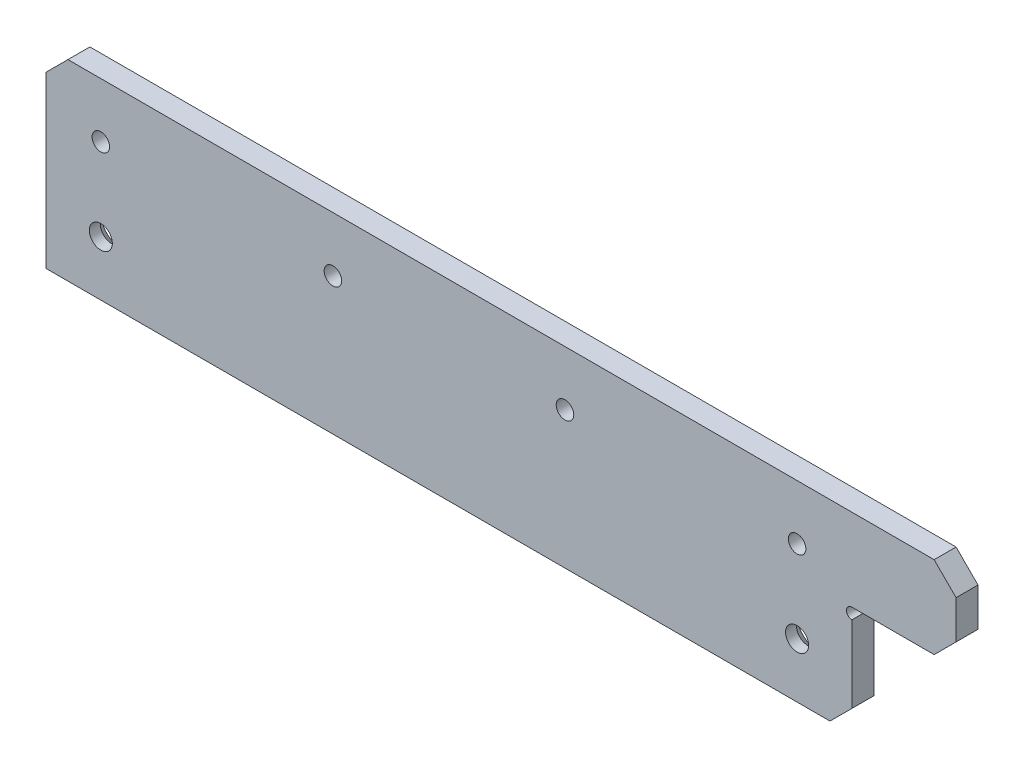
SolidWorks part; units mm, degrees
ref_plane "前视基准面" through (0, 0, 0) normal (0, 0, 1) x (1, 0, 0)
ref_plane "上视基准面" through (0, 0, 0) normal (0, 1, 0) x (1, 0, 0)
ref_plane "右视基准面" through (0, 0, 0) normal (1, 0, 0) x (0, 0, -1)
sketch "草图1" plane through (0, 0, 0) normal (0, 0, 1) x (1, 0, 0)
  line L1 (73.5, -17.5) -> (-73.5, -17.5)
  line L2 (73.5, -17.5) -> (73.5, 17.5)
  line L3 (73.5, 17.5) -> (-73.5, 17.5)
  line L4 (-73.5, -17.5) -> (-73.5, 17.5)
  line L5 (73.5, -17.5) -> (-73.5, 17.5) construction
  line L6 (73.5, 17.5) -> (-73.5, -17.5) construction
  point P0 (0, 0)
  dimension "D1" = 35
  dimension "D2" = 147
extrude "凸台-拉伸1" add sketch "草图1" along normal mid plane 4
sketch "草图2" plane through (0, 0, 2) normal (0, 0, 1) x (1, 0, 0)
  line L1 (73.5, 17.5) -> (92.5, 17.5)
  line L2 (73.5, 17.5) -> (73.5, 2.5)
  line L3 (73.5, 2.5) -> (92.5, 2.5)
  line L4 (92.5, 17.5) -> (92.5, 2.5)
  dimension "D1" = 15
  dimension "D2" = 19
extrude "凸台-拉伸2" add sketch "草图2" against normal blind 4
sketch "草图3" plane through (0, 0, 2) normal (0, 0, 1) x (1, 0, 0)
  line L0 (-63.5, -7.5) -> (63.5, -7.5) construction
  line L1 (-73.5, 17.5) -> (-73.5, -17.5) construction
  line L2 (-73.5, -17.5) -> (73.5, -17.5) construction
  line L3 (73.5, -17.5) -> (73.5, 2.5) construction
  circle A0 centre (-63.5, -7.5) radius 2.1
  circle A1 centre (63.5, -7.5) radius 2.1
  dimension "D1" = 4.2
  dimension "D2" = 10
  dimension "D4" = 10
  dimension "D3" = 10
extrude "切除-拉伸1" cut sketch "草图3" against normal through all
chamfer "倒角1" distance 4 angle 45 4 edges at (92.5, 2.5, 0) (73.5, -17.5, 0) (-73.5, 17.5, 0) (92.5, 17.5, 0)
sketch "草图4" plane through (0, 0, 2) normal (0, 0, 1) x (1, 0, 0)
  line L0 (73.5, -13.5) -> (73.5, 2.5) construction
  circle A0 centre (73.5, 1.5) radius 1
  dimension "D1" = 2
extrude "切除-拉伸2" cut sketch "草图4" against normal through all
sketch "草图5" plane through (0, 0, 2) normal (0, 0, 1) x (1, 0, 0)
  line L0 (-63.5, 7.5) -> (-21.1667, 7.5) construction
  line L1 (-21.1667, 7.5) -> (21.1667, 7.5) construction
  line L2 (21.1667, 7.5) -> (63.5, 7.5) construction
  line L3 (-73.5, 13.5) -> (-73.5, -17.5) construction
  line L4 (-73.5, -17.5) -> (69.5, -17.5) construction
  circle A0 centre (-63.5, 7.5) radius 1.6
  circle A1 centre (-21.1667, 7.5) radius 1.6
  circle A2 centre (21.1667, 7.5) radius 1.6
  circle A3 centre (63.5, 7.5) radius 1.6
  point P8 (0, 7.5)
  dimension "D1" = 3.2
  dimension "D2" = 10
  dimension "D3" = 25
extrude "切除-拉伸3" cut sketch "草图5" against normal through all
chamfer "倒角2" distance 2 angle 45 2 edges at (65.6, -7.5, -2) (-61.4, -7.5, -2)
